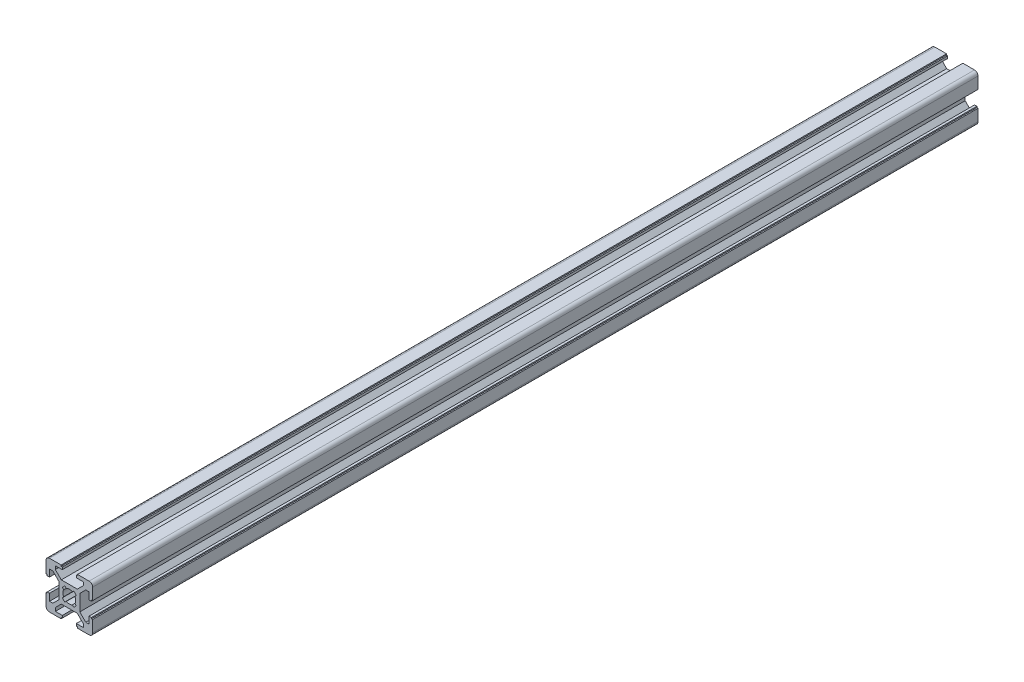
SolidWorks part; units mm, degrees
ref_plane "Ebene vorne" through (0, 0, 0) normal (0, 0, 1) x (1, 0, 0)
ref_plane "Ebene oben" through (0, 0, 0) normal (0, 1, 0) x (1, 0, 0)
ref_plane "Ebene rechts" through (0, 0, 0) normal (1, 0, 0) x (0, 0, -1)
sketch "Skizze1" plane through (0, 0, 0) normal (0, 0, 1) x (1, 0, 0)
  line L0 (-2.539, 1.0906) -> (-3.1036, 1.7634)
  line L1 (-3.1036, -2.1357) -> (-2.539, -1.4629)
  line L2 (-2.053, -3.1863) -> (-3.1036, -2.1357)
  line L3 (-1.3802, -2.6218) -> (-2.053, -3.1863)
  line L4 (1.8462, -3.1863) -> (1.1734, -2.6218)
  line L5 (2.8968, -2.1357) -> (1.8462, -3.1863)
  line L6 (2.3323, -1.4629) -> (2.8968, -2.1357)
  line L7 (2.8968, 1.7634) -> (2.3323, 1.0906)
  line L8 (1.8462, 2.814) -> (2.8968, 1.7634)
  line L9 (1.1734, 2.2495) -> (1.8462, 2.814)
  line L10 (-2.053, 2.814) -> (-1.3802, 2.2495)
  line L11 (-3.1036, 1.7634) -> (-2.053, 2.814)
  line L12 (9.8966, -8.6862) -> (9.8966, -3.6862)
  line L13 (9.8966, -3.6862) -> (9.3966, -3.6862)
  line L14 (9.3966, -3.6862) -> (9.3966, -3.1862)
  line L15 (9.3966, -3.1862) -> (8.3966, -3.1862)
  line L16 (8.3966, -3.1862) -> (8.3966, -6.1862)
  line L17 (8.3966, -6.1862) -> (6.9573, -6.1862)
  line L18 (6.9573, -6.1862) -> (4.3966, -3.6255)
  line L19 (4.3966, -3.6255) -> (4.3966, 3.2532)
  line L20 (4.3966, 3.2532) -> (6.9573, 5.8138)
  line L21 (6.9573, 5.8138) -> (8.3966, 5.8138)
  line L22 (8.3966, 5.8138) -> (8.3966, 2.8138)
  line L23 (8.3966, 2.8138) -> (9.3966, 2.8138)
  line L24 (9.3966, 2.8138) -> (9.3966, 3.3138)
  line L25 (9.3966, 3.3138) -> (9.8966, 3.3138)
  line L26 (9.8966, 3.3138) -> (9.8966, 8.3138)
  line L27 (8.3966, 9.8138) -> (3.3966, 9.8138)
  line L28 (3.3966, 9.8138) -> (3.3966, 9.3138)
  line L29 (3.3966, 9.3138) -> (2.8966, 9.3138)
  line L30 (2.8966, 9.3138) -> (2.8966, 8.3138)
  line L31 (2.8966, 8.3138) -> (5.8966, 8.3138)
  line L32 (5.8966, 8.3138) -> (5.8966, 6.8745)
  line L33 (5.8966, 6.8745) -> (3.336, 4.3138)
  line L34 (3.336, 4.3138) -> (-3.5427, 4.3138)
  line L35 (-3.5427, 4.3138) -> (-6.1034, 6.8745)
  line L36 (-6.1034, 6.8745) -> (-6.1034, 8.3138)
  line L37 (-6.1034, 8.3138) -> (-3.1034, 8.3138)
  line L38 (-3.1034, 8.3138) -> (-3.1034, 9.3138)
  line L39 (-3.1034, 9.3138) -> (-3.6034, 9.3138)
  line L40 (-3.6034, 9.3138) -> (-3.6034, 9.8138)
  line L41 (-3.6034, 9.8138) -> (-8.6034, 9.8138)
  line L42 (-10.1034, 8.3138) -> (-10.1034, 3.3138)
  line L43 (-10.1034, 3.3138) -> (-9.6034, 3.3138)
  line L44 (-9.6034, 3.3138) -> (-9.6034, 2.8138)
  line L45 (-9.6034, 2.8138) -> (-8.6034, 2.8138)
  line L46 (-8.6034, 2.8138) -> (-8.6034, 5.8138)
  line L47 (-8.6034, 5.8138) -> (-7.164, 5.8138)
  line L48 (-7.164, 5.8138) -> (-4.6034, 3.2532)
  line L49 (-4.6034, 3.2532) -> (-4.6034, -3.6255)
  line L50 (-4.6034, -3.6255) -> (-7.164, -6.1862)
  line L51 (-7.164, -6.1862) -> (-8.6034, -6.1862)
  line L52 (-8.6034, -6.1862) -> (-8.6034, -3.1862)
  line L53 (-8.6034, -3.1862) -> (-9.6034, -3.1862)
  line L54 (-9.6034, -3.1862) -> (-9.6034, -3.6862)
  line L55 (-9.6034, -3.6862) -> (-10.1034, -3.6862)
  line L56 (-10.1034, -3.6862) -> (-10.1034, -8.6862)
  line L57 (-8.6034, -10.1862) -> (-3.6034, -10.1862)
  line L58 (-3.6034, -10.1862) -> (-3.6034, -9.6862)
  line L59 (-3.6034, -9.6862) -> (-3.1034, -9.6862)
  line L60 (-3.1034, -9.6862) -> (-3.1034, -8.6862)
  line L61 (-3.1034, -8.6862) -> (-6.1034, -8.6862)
  line L62 (-6.1034, -8.6862) -> (-6.1034, -7.2468)
  line L63 (-6.1034, -7.2468) -> (-3.5427, -4.6862)
  line L64 (-3.5427, -4.6862) -> (3.336, -4.6862)
  line L65 (3.336, -4.6862) -> (5.8966, -7.2468)
  line L66 (5.8966, -7.2468) -> (5.8966, -8.6862)
  line L67 (5.8966, -8.6862) -> (2.8966, -8.6862)
  line L68 (2.8966, -8.6862) -> (2.8966, -9.6862)
  line L69 (2.8966, -9.6862) -> (3.3966, -9.6862)
  line L70 (3.3966, -9.6862) -> (3.3966, -10.1862)
  line L71 (3.3966, -10.1862) -> (8.3966, -10.1862)
  arc A0 (8.3966, -10.1862) -> (9.8966, -8.6862) centre (8.3966, -8.6862) ccw
  arc A1 (9.8966, 8.3138) -> (8.3966, 9.8138) centre (8.3966, 8.3138) ccw
  arc A2 (-8.6034, 9.8138) -> (-10.1034, 8.3138) centre (-8.6034, 8.3138) ccw
  arc A3 (-10.1034, -8.6862) -> (-8.6034, -10.1862) centre (-8.6034, -8.6862) ccw
  arc A4 (-2.539, 1.0906) -> (-2.539, -1.4629) centre (-0.1034, -0.1862) ccw
  arc A5 (-1.3802, -2.6218) -> (1.1734, -2.6218) centre (-0.1034, -0.1862) ccw
  arc A6 (2.3323, -1.4629) -> (2.3323, 1.0906) centre (-0.1034, -0.1862) ccw
  arc A7 (1.1734, 2.2495) -> (-1.3802, 2.2495) centre (-0.1034, -0.1862) ccw
extrude "Aufsatz-Linear austragen1" add sketch "Skizze1" along normal blind 380
